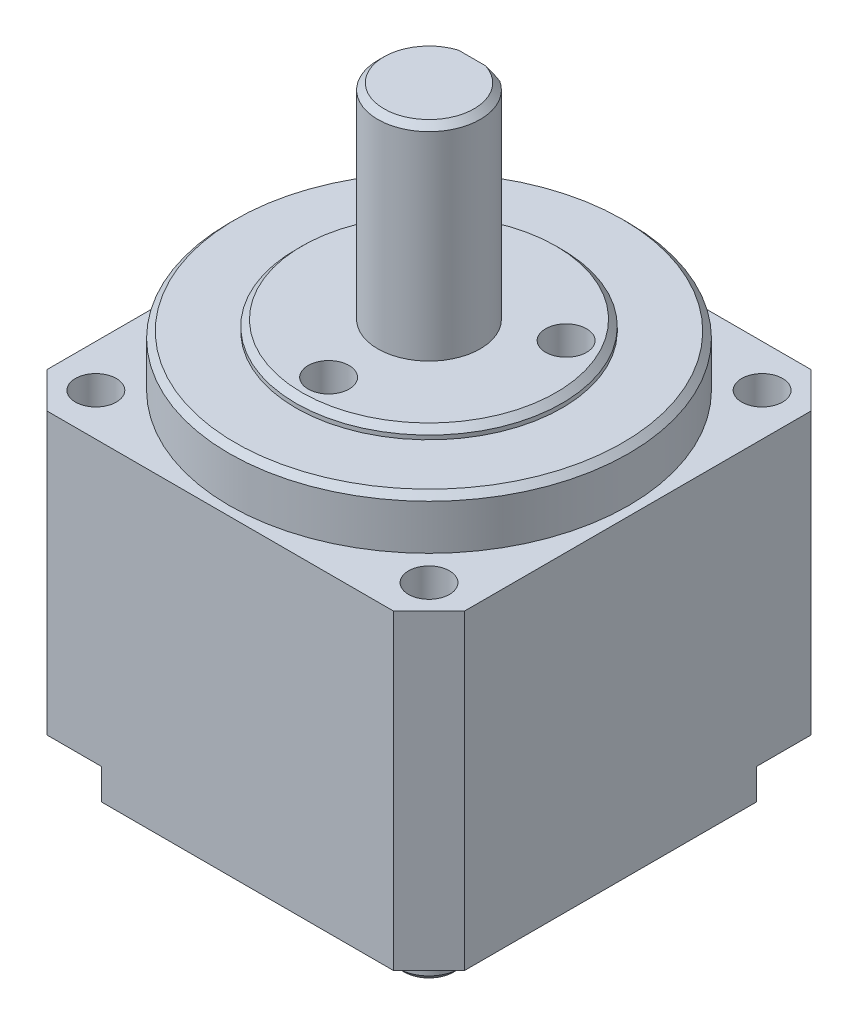
SolidWorks part; units mm, degrees
ref_plane "前视基准面" through (0, 0, 0) normal (0, 0, 1) x (1, 0, 0)
ref_plane "上视基准面" through (0, 0, 0) normal (0, 1, 0) x (1, 0, 0)
ref_plane "右视基准面" through (0, 0, 0) normal (1, 0, 0) x (0, 0, -1)
other "Configuration Table"
sketch "草图1" plane through (0, 0, 0) normal (0, 1, 0) x (1, 0, 0)
  line L1 (10.2, -10.2) -> (-10.2, -10.2)
  line L2 (10.2, -10.2) -> (10.2, 10.2)
  line L3 (10.2, 10.2) -> (-10.2, 10.2)
  line L4 (-10.2, -10.2) -> (-10.2, 10.2)
  line L5 (10.2, -10.2) -> (-10.2, 10.2) construction
  line L6 (10.2, 10.2) -> (-10.2, -10.2) construction
  point P0 (0, 0)
  dimension "D1" = 20.4
  dimension "D2" = 20.4
extrude "凸台-拉伸1" add sketch "草图1" along normal blind 15.2
sketch "草图2" plane through (0, 15.2, 0) normal (0, 1, 0) x (1, 0, 0)
  circle A0 centre (0, 0) radius 9.75
  dimension "D1" = 19.5
extrude "凸台-拉伸2" add sketch "草图2" along normal blind 2.5
sketch "草图3" plane through (0, 17.7, 0) normal (0, 1, 0) x (1, 0, 0)
  circle A0 centre (0, 0) radius 6.5
  dimension "D1" = 13
extrude "凸台-拉伸3" add sketch "草图3" along normal blind 0.5
chamfer "倒角1" distance 0.3 angle 45 1 edges at (0, 18.2, 6.5)
chamfer "倒角2" distance 0.3 angle 45 1 edges at (0, 17.7, 9.75)
sketch "草图4" plane through (0, 18.2, 0) normal (0, 1, 0) x (1, 0, 0)
  circle A0 centre (0, 0) radius 2.5
  dimension "D1" = 5
extrude "凸台-拉伸4" add sketch "草图4" along normal blind 10
sketch "草图5" plane through (0, 0, 0) normal (0, -1, 0) x (1, 0, 0)
  circle A0 centre (0, 0) radius 4.5
  dimension "D1" = 9
extrude "凸台-拉伸5" add sketch "草图5" along normal blind 0.8
sketch "草图6" plane through (0, -0.8, 0) normal (0, -1, 0) x (1, 0, 0)
  circle A0 centre (0, 0) radius 1.5
  dimension "D1" = 3
extrude "凸台-拉伸6" add sketch "草图6" along normal blind 8
chamfer "倒角3" distance 0.3 angle 45 2 edges at (0, -0.8, -4.5) (0, -8.8, -1.5)
sketch "草图7" plane through (0, 0, 0) normal (0, -1, 0) x (1, 0, 0)
  line L0 (-10.2, 5.8) -> (-8.5, 5.8)
  line L1 (-10.2, -10.2) -> (-10.2, 10.2) construction
  line L2 (-5.8, 8.5) -> (-5.8, 10.2)
  line L3 (-10.2, 10.2) -> (10.2, 10.2) construction
  line L4 (-5.8, 10.2) -> (-10.2, 10.2)
  line L5 (-10.2, 10.2) -> (-10.2, 5.8)
  line L6 (10.2, -10.2) -> (10.2, -5.8)
  line L7 (10.2, 10.2) -> (10.2, -10.2) construction
  line L8 (10.2, -5.8) -> (8.5, -5.8)
  line L9 (5.8, -8.5) -> (5.8, -10.2)
  line L10 (10.2, -10.2) -> (-10.2, -10.2) construction
  line L11 (5.8, -10.2) -> (10.2, -10.2)
  arc A0 (-8.5, 5.8) -> (-5.8, 8.5) centre (-8.5, 8.5) ccw
  arc A1 (8.5, -5.8) -> (5.8, -8.5) centre (8.5, -8.5) ccw
  dimension "D3" = 2.7
  dimension "D6" = 2.7
  dimension "D1" = 4.4
  dimension "D2" = 4.4
  dimension "D4" = 4.4
  dimension "D5" = 4.4
extrude "切除-拉伸1" cut sketch "草图7" against normal blind 1.5
sketch "草图8" plane through (0, 15.2, 0) normal (0, 1, 0) x (1, 0, 0)
  line L1 (8.1317, -8.1317) -> (-8.1317, -8.1317) construction
  line L2 (8.1317, -8.1317) -> (8.1317, 8.1317) construction
  line L3 (8.1317, 8.1317) -> (-8.1317, 8.1317) construction
  line L4 (-8.1317, -8.1317) -> (-8.1317, 8.1317) construction
  line L5 (8.1317, -8.1317) -> (-8.1317, 8.1317) construction
  line L6 (8.1317, 8.1317) -> (-8.1317, -8.1317) construction
  circle A0 centre (0, 0) radius 11.5 construction
  circle A1 centre (-8.1317, 8.1317) radius 1
  circle A2 centre (8.1317, 8.1317) radius 1
  circle A3 centre (8.1317, -8.1317) radius 1
  circle A4 centre (-8.1317, -8.1317) radius 1
  dimension "D1" = 23
  dimension "D2" = 2
extrude "切除-拉伸2" cut sketch "草图8" against normal blind 6
sketch "草图9" plane through (0, 9.2, 0) normal (0, 1, 0) x (1, 0, 0)
  circle A0 centre (8.1317, -8.1317) radius 1.25
  circle A1 centre (8.1317, 8.1317) radius 1.25
  circle A2 centre (-8.1317, 8.1317) radius 1.25
  circle A3 centre (-8.1317, -8.1317) radius 1.25
  dimension "D1" = 2.5
extrude "切除-拉伸3" cut sketch "草图9" against normal blind 1.5
sketch "草图10" plane through (0, 18.2, 0) normal (0, 1, 0) x (1, 0, 0)
  line L0 (0, 0) -> (-11.9957, 0) construction
  line L1 (0, 0) -> (0, -7.4684) construction
  circle A4 centre (0, -4.9) radius 1
  circle A5 centre (-4.2435, 2.45) radius 1
  circle A6 centre (4.2435, 2.45) radius 1
  point P4 (0, 0)
  point P12 (0, 0)
  point P14 (0, 0)
  dimension "D1" = 3
  dimension "D3" = 2
  dimension "D4" = 4.9
extrude "切除-拉伸4" cut sketch "草图10" against normal blind 4
sketch "草图11" plane through (0, 14.2, 0) normal (0, 1, 0) x (1, 0, 0)
  circle A4 centre (0, -4.9) radius 0.8
  circle A5 centre (-4.2435, 2.45) radius 0.8
  circle A6 centre (4.2435, 2.45) radius 0.8
  point P4 (-1.9941, 0.5272)
  point P6 (0, 0)
  point P13 (0, 0)
  dimension "D1" = 1.6
  dimension "D2" = 3
extrude "切除-拉伸5" cut sketch "草图11" against normal blind 1.2
chamfer "倒角4" distance 1.743 angle 45 4 edges at (10.2, 8.35, -10.2) (-10.2, 7.6, -10.2) (-10.2, 8.35, 10.2) (10.2, 7.6, 10.2)
chamfer "倒角5" distance 0.3 angle 45 1 edges at (0, 28.2, 2.5)
sketch "草图12" plane through (0, 28.2, 0) normal (0, 1, 0) x (1, 0, 0)
  line L0 (-1.3565, 2.1) -> (1.3565, 2.1)
  circle A0 centre (0, 0) radius 2.5 construction
  arc A1 (1.3565, 2.1) -> (-1.3565, 2.1) centre (0, 0) ccw
  dimension "D1" = 2.1
extrude "切除-拉伸6" cut sketch "草图12" against normal blind 9
sketch "草图13" plane through (0, -8.8, 0) normal (0, -1, 0) x (1, 0, 0)
  line L0 (-1.0198, -1.1) -> (1.0198, -1.1)
  circle A0 centre (0, 0) radius 1.5 construction
  arc A1 (-1.0198, -1.1) -> (1.0198, -1.1) centre (0, 0) ccw
  dimension "D1" = 1.1
extrude "切除-拉伸7" cut sketch "草图13" against normal blind 7
